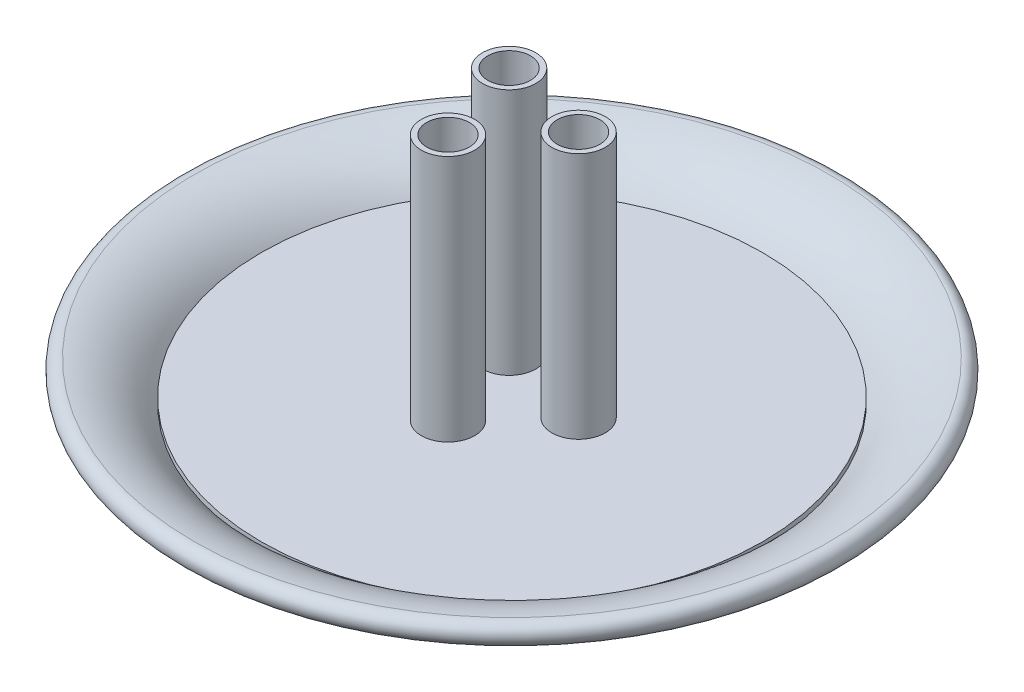
SolidWorks part; units mm, degrees
ref_plane "Front Plane" through (0, 0, 0) normal (0, 0, 1) x (1, 0, 0)
ref_plane "Top Plane" through (0, 0, 0) normal (0, 1, 0) x (1, 0, 0)
ref_plane "Right Plane" through (0, 0, 0) normal (1, 0, 0) x (0, 0, -1)
sketch "Sketch1" plane through (0, 0, 0) normal (0, 0, 1) x (1, 0, 0)
  line L3 (3.1193, -4.8165) -> (13.1193, -4.8165)
  line L6 (3.2579, -2.8165) -> (13.1193, -2.8165)
  line L7 (13.1193, -2.8165) -> (13.1193, -4.8165)
  arc A0 (-16.8807, 5.1835) -> (-11.8807, 2.1835) centre (-17.5986, -1.6796) cw
  arc A1 (3.1193, -4.8165) -> (-11.8807, 2.1835) centre (6.9048, 22.8668) cw
  arc A2 (-16.6727, 7.1726) -> (-10.3722, 3.5164) centre (-17.5986, -1.6796) cw
  arc A3 (3.2579, -2.8165) -> (-10.3722, 3.5164) centre (6.9048, 22.8668) cw
  arc A4 (-16.8807, 5.1835) -> (-16.6727, 7.1726) centre (-16.7767, 6.1781) cw
  dimension "D1" = 2
  dimension "D5" = 10
revolve "Revolve1" add sketch "Sketch1" angle 360 about L7
sketch "Sketch2" plane through (0, -2.8165, 0) normal (0, 1, 0) x (1, 0, 0)
  circle A0 centre (9.4558, 3.4028) radius 2.5
  circle A1 centre (13.1193, 0) radius 9.8613 construction
  circle A2 centre (9.4558, 3.4028) radius 2
  circle A3 centre (17.8979, 1.4713) radius 2.5
  circle A4 centre (17.8979, 1.4713) radius 2
  circle A5 centre (12.0041, -4.8741) radius 2.5
  circle A6 centre (12.0041, -4.8741) radius 2
  dimension "D1" = 5
  dimension "D2" = 5
  dimension "D3" = 4
  dimension "D4" = 3
extrude "Boss-Extrude2" add sketch "Sketch2" along normal blind 30
ref_plane "Plane1" through (0, 2, 0) normal (0, 1, 0) x (1, 0, 0)
sketch "Sketch4" plane through (0, 2, 0) normal (0, 1, 0) x (1, 0, 0)
  circle A0 centre (13.1193, 0) radius 23.4914
extrude "Boss-Extrude4" add sketch "Sketch4" along normal blind 2
